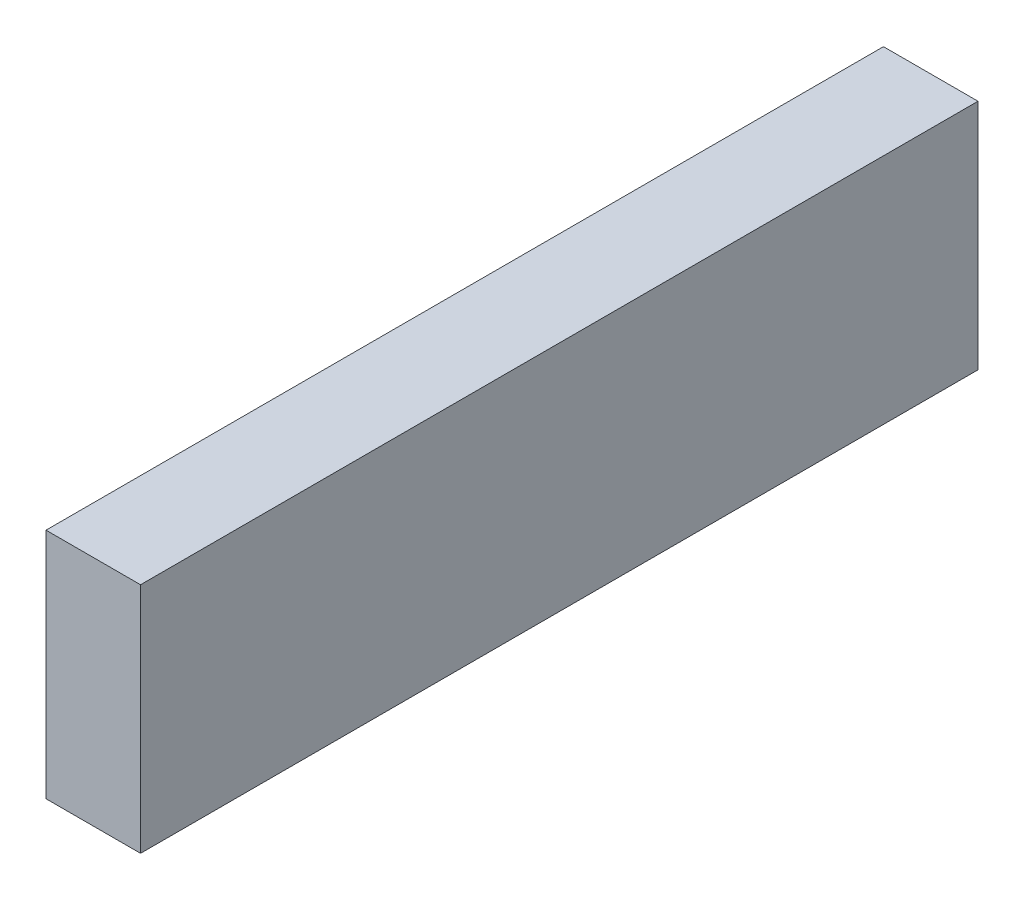
SolidWorks part; units mm, degrees
ref_plane "Alzado" through (0, 0, 0) normal (0, 0, 1) x (1, 0, 0)
ref_plane "Planta" through (0, 0, 0) normal (0, 1, 0) x (1, 0, 0)
ref_plane "Vista lateral" through (0, 0, 0) normal (1, 0, 0) x (0, 0, -1)
sketch "Croquis1" plane through (0, 0, 0) normal (0, 0, 1) x (1, 0, 0)
  line L1 (0, 0) -> (101.6, 0)
  line L2 (0, 0) -> (0, -250)
  line L3 (0, -250) -> (101.6, -250)
  line L4 (101.6, 0) -> (101.6, -250)
  dimension "D1" = 250
  dimension "D2" = 101.6
extrude "Saliente-Extruir1" add sketch "Croquis1" along normal blind 900
